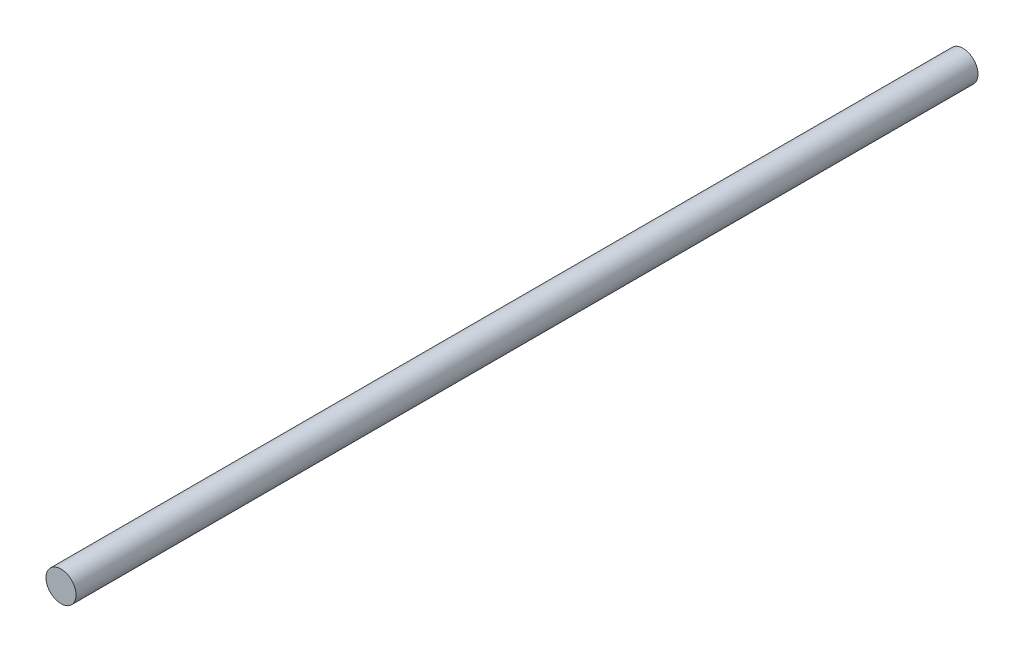
SolidWorks part; units mm, degrees
material "AISI 1020"
ref_plane "前视基准面" through (0, 0, 0) normal (0, 0, 1) x (1, 0, 0)
ref_plane "上视基准面" through (0, 0, 0) normal (0, 1, 0) x (1, 0, 0)
ref_plane "右视基准面" through (0, 0, 0) normal (1, 0, 0) x (0, 0, -1)
sketch "草图1" plane through (0, 0, 0) normal (0, 0, 1) x (1, 0, 0)
  circle A0 centre (0, 0) radius 2.5
  dimension "D1" = 5
extrude "凸台-拉伸1" add sketch "草图1" along normal blind 150
